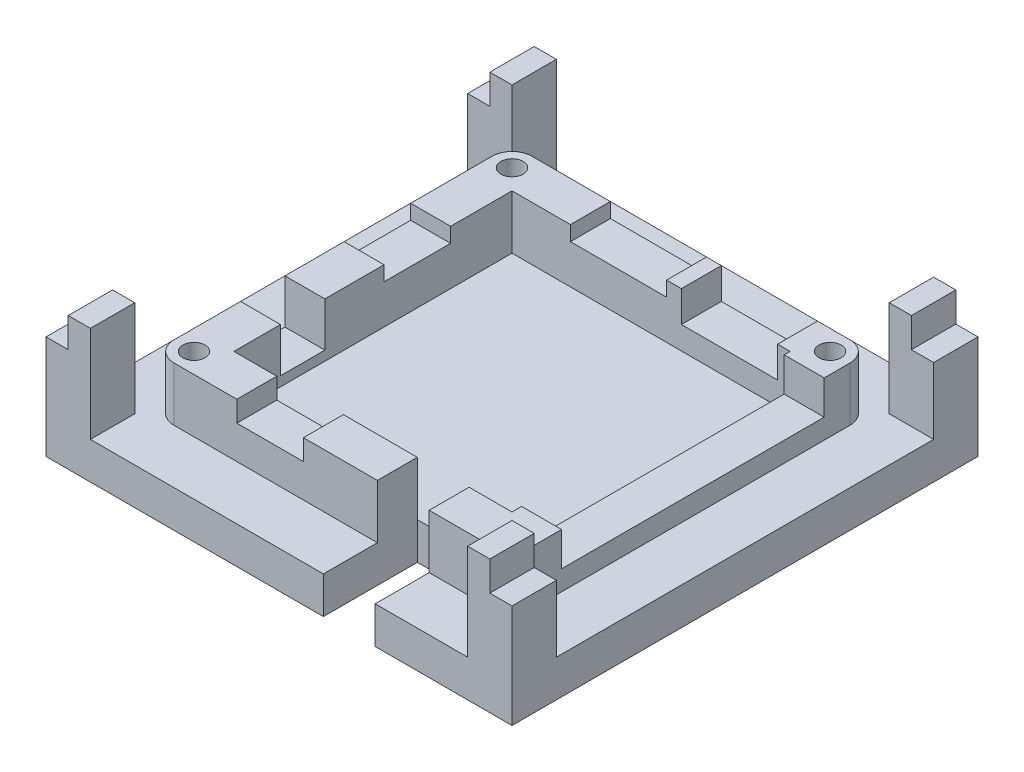
SolidWorks part; units mm, degrees
ref_plane "Front Plane" through (0, 0, 0) normal (0, 0, 1) x (1, 0, 0)
ref_plane "Top Plane" through (0, 0, 0) normal (0, 1, 0) x (1, 0, 0)
ref_plane "Right Plane" through (0, 0, 0) normal (1, 0, 0) x (0, 0, -1)
sketch "Sketch1" plane through (0, 0, 0) normal (0, 1, 0) x (1, 0, 0)
  line L1 (0, 0) -> (63, 0)
  line L2 (0, 0) -> (0, 63)
  line L3 (0, 63) -> (63, 63)
  line L4 (63, 0) -> (63, 63)
  dimension "D1" = 63
  dimension "D2" = 63
extrude "Boss-Extrude1" add sketch "Sketch1" along normal blind 5
sketch "Sketch2" plane through (0, 5, 0) normal (0, 1, 0) x (1, 0, 0)
  line L1 (0, 63) -> (6, 63)
  line L2 (0, 63) -> (0, 57)
  line L3 (0, 57) -> (6, 57)
  line L4 (6, 63) -> (6, 57)
  line L5 (0, 0) -> (6, 0)
  line L6 (0, 0) -> (0, 6)
  line L7 (0, 6) -> (6, 6)
  line L8 (6, 0) -> (6, 6)
  line L9 (63, 63) -> (57, 63)
  line L10 (63, 63) -> (63, 57)
  line L11 (63, 57) -> (57, 57)
  line L12 (57, 63) -> (57, 57)
  line L13 (63, 0) -> (57, 0)
  line L14 (63, 0) -> (63, 6)
  line L15 (63, 6) -> (57, 6)
  line L16 (57, 0) -> (57, 6)
  dimension "D1" = 6
extrude "Boss-Extrude2" add sketch "Sketch2" along normal blind 13
sketch "Sketch3" plane through (0, 5, 0) normal (0, 1, 0) x (1, 0, 0)
  line L0 (0, 57) -> (0, 6) construction
  line L2 (57, 63) -> (6, 63) construction
  circle A0 centre (53, 10) radius 1.5
  circle A1 centre (10, 10) radius 1.5
  circle A2 centre (10, 53) radius 1.5
  circle A3 centre (53, 53) radius 1.5
  dimension "D3" = 3
  dimension "D4" = 10
  dimension "D5" = 10
  dimension "D1" = 43
  dimension "D2" = 43
extrude "Cut-Extrude1" cut sketch "Sketch3" against normal up to surface (5 mm away) up to face at (31.5, 0, -31.5)
sketch "Sketch4" plane through (0, 5, 0) normal (0, 1, 0) x (1, 0, 0)
  circle A0 centre (10, 10) radius 2.7
  circle A1 centre (10, 53) radius 2.7
  circle A2 centre (53, 10) radius 2.7
  circle A3 centre (53, 53) radius 2.7
  circle A4 centre (53, 10) radius 1.5
  circle A5 centre (53, 53) radius 1.5
  circle A6 centre (10, 53) radius 1.5
  circle A7 centre (10, 10) radius 1.5
  dimension "D1" = 5.4
extrude "Boss-Extrude3" add sketch "Sketch4" along normal blind 7.3
sketch "Sketch5" plane through (0, 5, 0) normal (0, 1, 0) x (1, 0, 0)
  line L0 (10, 7.3) -> (53, 7.3)
  line L1 (53, 12.7) -> (10, 12.7)
  arc A0 (10, 12.7) -> (10, 7.3) centre (10, 10) cw
  circle A1 centre (10, 10) radius 2.7 construction
  arc A2 (53, 12.7) -> (53, 7.3) centre (53, 10) ccw
  circle A3 centre (53, 10) radius 2.7 construction
extrude "Boss-Extrude4" add sketch "Sketch5" along normal up to surface (7.3 mm away) up to face at (10, 12.3, -7.3)
sketch "Sketch6" plane through (0, 12.3, 0) normal (0, 1, 0) x (1, 0, 0)
  line L0 (53, 12.7) -> (10, 12.7) construction
  line L1 (18.5, 12.7) -> (27.5, 12.7)
  line L2 (18.5, 12.7) -> (18.5, 7.3)
  line L3 (18.5, 7.3) -> (27.5, 7.3)
  line L4 (27.5, 12.7) -> (27.5, 7.3)
  line L5 (10, 7.3) -> (53, 7.3) construction
  circle A0 centre (10, 10) radius 1.5 construction
  dimension "D1" = 8.5
  dimension "D2" = 9
extrude "Cut-Extrude2" cut sketch "Sketch6" against normal blind 2.8
sketch "Sketch7" plane through (0, 12.3, 0) normal (0, 1, 0) x (1, 0, 0)
  line L0 (53, 12.7) -> (27.5, 12.7) construction
  line L1 (37.5, 12.7) -> (44.5, 12.7)
  line L2 (37.5, 12.7) -> (37.5, 0)
  line L3 (37.5, 0) -> (44.5, 0)
  line L4 (44.5, 12.7) -> (44.5, 0)
  line L6 (27.5, 7.3) -> (27.5, 12.7) construction
  line L7 (6, 0) -> (57, 0) construction
  dimension "D1" = 10
  dimension "D2" = 7
  dimension "D3" = 0
extrude "Cut-Extrude3" cut sketch "Sketch7" against normal up to surface (12.3 mm away) up to face at (53, 0, -54.5)
sketch "Sketch8" plane through (0, 5, 0) normal (0, 1, 0) x (1, 0, 0)
  line L0 (53, 12.7) -> (44.5, 12.7) construction
  line L1 (55.7, 53) -> (55.7, 10)
  line L2 (50.3, 50.3) -> (50.3, 12.7)
  line L3 (50.3, 12.7) -> (53, 12.7)
  line L4 (7.3, 10) -> (7.3, 53)
  line L5 (10, 55.7) -> (53, 55.7)
  line L6 (12.7, 50.3) -> (12.7, 12.7)
  line L7 (12.7, 12.7) -> (10, 12.7)
  line L8 (12.7, 50.3) -> (50.3, 50.3)
  arc A0 (55.7, 10) -> (53, 12.7) centre (53, 10) ccw
  arc A1 (53, 7.3) -> (53, 12.7) centre (53, 10) ccw construction
  arc A2 (55.7, 53) -> (50.3, 53) centre (53, 53) cw
  circle A3 centre (53, 53) radius 2.7 construction
  arc A4 (10, 55.7) -> (10, 50.3) centre (10, 53) cw
  circle A5 centre (10, 53) radius 2.7 construction
  arc A6 (53, 55.7) -> (50.3, 53) centre (53, 53) ccw
  arc A7 (10, 50.3) -> (7.3, 53) centre (10, 53) cw
  arc A8 (7.3, 10) -> (10, 12.7) centre (10, 10) cw
  arc A9 (10, 12.7) -> (10, 7.3) centre (10, 10) ccw construction
extrude "Boss-Extrude5" add sketch "Sketch8" along normal up to surface (7.3 mm away) up to face at (13.575, 12.3, -10)
sketch "Sketch9" plane through (0, 12.3, 0) normal (0, 1, 0) x (1, 0, 0)
  line L0 (50.3, 50.3) -> (50.3, 12.7) construction
  line L1 (50.3, 14) -> (55.7, 14)
  line L2 (50.3, 14) -> (50.3, 49.5)
  line L3 (50.3, 49.5) -> (55.7, 49.5)
  line L4 (55.7, 14) -> (55.7, 49.5)
  line L5 (55.7, 10) -> (55.7, 53) construction
  circle A0 centre (53, 53) radius 1.5 construction
  circle A1 centre (53, 10) radius 1.5 construction
  dimension "D1" = 3.5
  dimension "D2" = 4
extrude "Cut-Extrude4" cut sketch "Sketch9" against normal blind 4.6
sketch "Sketch10" plane through (0, 12.3, 0) normal (0, 1, 0) x (1, 0, 0)
  line L0 (53, 55.7) -> (10, 55.7) construction
  line L1 (48.6, 55.7) -> (35.6, 55.7)
  line L2 (48.6, 55.7) -> (48.6, 50.3)
  line L3 (48.6, 50.3) -> (35.6, 50.3)
  line L4 (35.6, 55.7) -> (35.6, 50.3)
  line L5 (12.7, 50.3) -> (50.3, 50.3) construction
  circle A0 centre (53, 53) radius 1.5 construction
  dimension "D1" = 13
  dimension "D2" = 4.4
extrude "Cut-Extrude5" cut sketch "Sketch10" against normal blind 4.2
sketch "Sketch11" plane through (0, 12.3, 0) normal (0, 1, 0) x (1, 0, 0)
  line L0 (35.6, 55.7) -> (10, 55.7) construction
  line L1 (20.6, 55.7) -> (33.6, 55.7)
  line L2 (20.6, 55.7) -> (20.6, 50.3)
  line L3 (20.6, 50.3) -> (33.6, 50.3)
  line L4 (33.6, 55.7) -> (33.6, 50.3)
  line L5 (12.7, 50.3) -> (35.6, 50.3) construction
  line L6 (35.6, 55.7) -> (35.6, 50.3) construction
  dimension "D1" = 2
  dimension "D2" = 13
extrude "Cut-Extrude6" cut sketch "Sketch11" against normal blind 2
sketch "Sketch12" plane through (0, 12.3, 0) normal (0, 1, 0) x (1, 0, 0)
  line L0 (7.3, 53) -> (7.3, 10) construction
  line L1 (7.3, 42) -> (12.7, 42)
  line L2 (7.3, 42) -> (7.3, 33)
  line L3 (7.3, 33) -> (12.7, 33)
  line L4 (12.7, 42) -> (12.7, 33)
  line L5 (12.7, 12.7) -> (12.7, 50.3) construction
  circle A0 centre (10, 53) radius 1.5 construction
  dimension "D1" = 11
  dimension "D2" = 9
extrude "Cut-Extrude7" cut sketch "Sketch12" against normal blind 2
sketch "Sketch13" plane through (0, 12.3, 0) normal (0, 1, 0) x (1, 0, 0)
  line L0 (7.3, 33) -> (7.3, 10) construction
  line L1 (7.3, 25) -> (12.7, 25)
  line L2 (7.3, 25) -> (7.3, 19)
  line L3 (7.3, 19) -> (12.7, 19)
  line L4 (12.7, 25) -> (12.7, 19)
  line L5 (12.7, 12.7) -> (12.7, 33) construction
  line L6 (7.3, 33) -> (12.7, 33) construction
  dimension "D1" = 8
  dimension "D2" = 6
extrude "Cut-Extrude8" cut sketch "Sketch13" against normal blind 6
sketch "Sketch14" plane through (0, 18, 0) normal (0, 1, 0) x (1, 0, 0)
  line L0 (0, 0) -> (6, 0) construction
  line L1 (0, 6) -> (3, 6)
  line L2 (0, 6) -> (0, 0)
  line L3 (0, 0) -> (3, 0)
  line L4 (3, 6) -> (3, 0)
  line L5 (57, 0) -> (63, 0) construction
  line L6 (63, 6) -> (60, 6)
  line L7 (63, 6) -> (63, 0)
  line L8 (63, 0) -> (60, 0)
  line L9 (60, 6) -> (60, 0)
  line L10 (57, 57) -> (63, 57) construction
  line L11 (63, 63) -> (60, 63)
  line L12 (63, 63) -> (63, 57)
  line L13 (63, 57) -> (60, 57)
  line L14 (60, 63) -> (60, 57)
  line L16 (0, 57) -> (6, 57) construction
  line L17 (0, 63) -> (3, 63)
  line L18 (0, 63) -> (0, 57)
  line L19 (0, 57) -> (3, 57)
  line L20 (3, 63) -> (3, 57)
extrude "Cut-Extrude9" cut sketch "Sketch14" against normal blind 4
